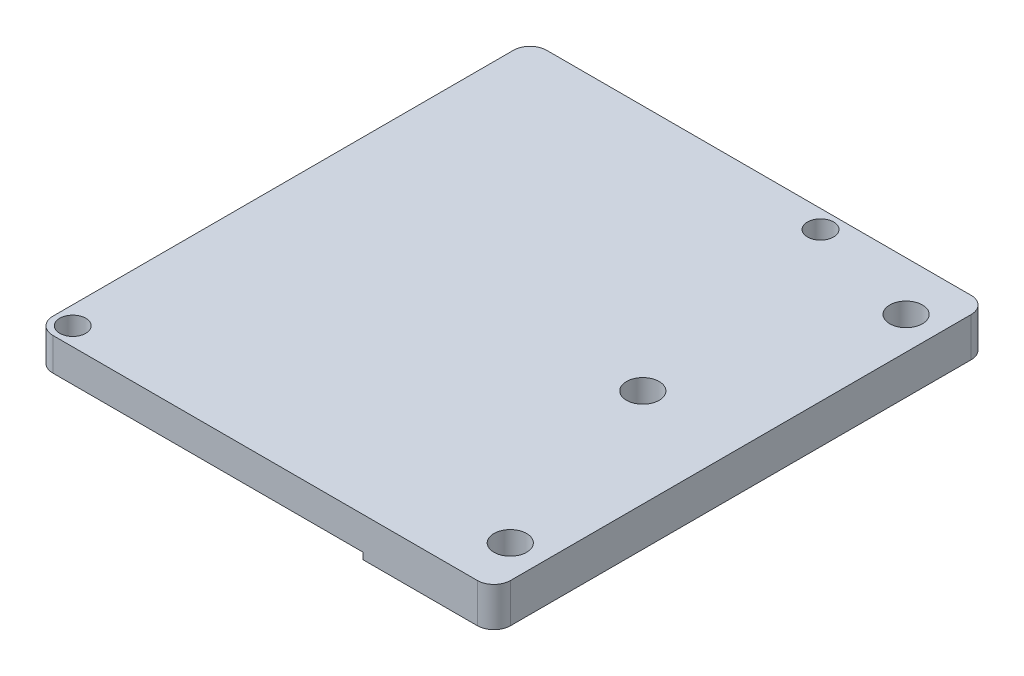
SolidWorks part; units mm, degrees
ref_plane "Front" through (0, 0, 0) normal (0, 0, 1) x (1, 0, 0)
ref_plane "Top" through (0, 0, 0) normal (0, 1, 0) x (1, 0, 0)
ref_plane "Right" through (0, 0, 0) normal (1, 0, 0) x (0, 0, -1)
sketch "Sketch1" plane through (0, 0, 0) normal (0, 1, 0) x (1, 0, 0)
  line L1 (-70.038, 75.565) -> (70.038, 75.565)
  line L2 (-70.038, 75.565) -> (-70.038, -75.565)
  line L3 (-70.038, -75.565) -> (70.038, -75.565)
  line L4 (70.038, 75.565) -> (70.038, -75.565)
  line L5 (-70.038, 75.565) -> (70.038, -75.565) construction
  line L6 (-70.038, -75.565) -> (70.038, 75.565) construction
  point P0 (0, 0)
  dimension "D1" = 140.076
  dimension "D2" = 151.13
extrude "Boss-Extrude1" add sketch "Sketch1" along normal blind 12
sketch "Sketch2" plane through (0, 0, 0) normal (0, -1, 0) x (1, 0, 0)
  line L5 (70.038, -75.565) -> (-70.038, -75.565) construction
  line L6 (-70.038, 75.565) -> (30.038, 75.565)
  line L8 (-70.038, 75.565) -> (-70.038, -75.565)
  line L9 (-70.038, -75.565) -> (30.038, -75.565)
  line L10 (30.038, 75.565) -> (30.038, -75.565)
  line L11 (-70.038, 75.565) -> (30.038, -75.565) construction
  line L12 (-70.038, -75.565) -> (30.038, 75.565) construction
  line L13 (70.038, 75.565) -> (70.038, -75.565) construction
  point P4 (-20, 0)
  dimension "D1" = 40
extrude "Cut-Extrude1" cut sketch "Sketch2" against normal blind 2
sketch "Sketch3" plane through (0, 12, 0) normal (0, 1, 0) x (1, 0, 0)
  circle A0 centre (24.45, 69.977) radius 4
  circle A1 centre (-64.45, -69.977) radius 4
  dimension "D1" = 8
  dimension "D2" = 8
extrude "Cut-Extrude2" cut sketch "Sketch3" against normal blind 8
sketch "Sketch4" plane through (0, 12, 0) normal (0, 1, 0) x (1, 0, 0)
  line L0 (60.038, 75.565) -> (60.038, -75.565) construction
  line L1 (70.038, 75.565) -> (-70.038, 75.565) construction
  line L2 (-70.038, -75.565) -> (70.038, -75.565) construction
  line L3 (40.038, 75.565) -> (40.038, -75.565) construction
  line L4 (70.038, -75.565) -> (70.038, 75.565) construction
  circle A0 centre (40.038, 0) radius 2.75
  circle A1 centre (60.038, -60.565) radius 2.75
  circle A2 centre (60.038, 60.565) radius 2.75
  dimension "D3" = 5.5
  dimension "D4" = 15
  dimension "D5" = 15
  dimension "D1" = 10
  dimension "D2" = 20
extrude "Cut-Extrude3" cut sketch "Sketch4" against normal up to next
fillet "Fillet1" radius 5.08 4 edges at (70.038, 6, 75.565) (-70.038, 7, 75.565) (-70.038, 7, -75.565) (70.038, 6, -75.565)
sketch "Sketch5" plane through (0, 12, 0) normal (0, 1, 0) x (1, 0, 0)
  circle A0 centre (60.038, 60.565) radius 5
  circle A1 centre (40.038, 0) radius 5
  circle A2 centre (60.038, -60.565) radius 5
  dimension "D1" = 10
extrude "Cut-Extrude4" cut sketch "Sketch5" against normal offset from surface (9 mm away) 3 up to face at (40.038, 0, 2.75)
